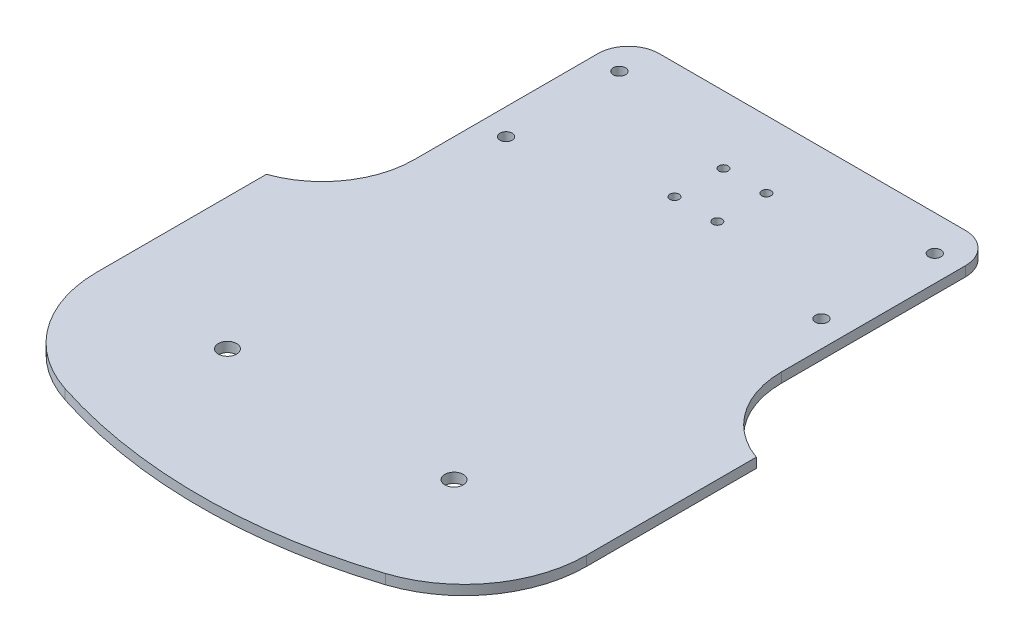
SolidWorks part; units mm, degrees
other "main"
material "Skleněné vlákno-A"
ref_plane "Přední rovina" through (0, 0, 0) normal (0, 0, 1) x (1, 0, 0)
ref_plane "Horní rovina" through (0, 0, 0) normal (0, 1, 0) x (1, 0, 0)
ref_plane "Pravá rovina" through (0, 0, 0) normal (1, 0, 0) x (0, 0, -1)
sketch "Skica1" plane through (0, 0, 0) normal (0, 1, 0) x (1, 0, 0)
  line L0 (0, 0) -> (-30, 0) construction
  line L1 (-25, 15) -> (25, 15)
  line L2 (-30, 10) -> (-30, -20)
  line L3 (0, -85) -> (-40, -85) construction
  line L4 (30, 10) -> (30, -20)
  line L5 (-40, -61.8466) -> (-40, -34.1421)
  line L6 (0, -154.3556) -> (0, 117.2396) construction
  line L7 (40, -61.8466) -> (40, -34.1421)
  arc A0 (-30, -20) -> (-40, -34.1421) centre (-45, -20) cw
  arc A1 (-25, 15) -> (-30, 10) centre (-25, 10) ccw
  arc A2 (26.1538, -80.8763) -> (-26.1538, -80.8763) centre (0, 0) cw
  arc A3 (25, 15) -> (30, 10) centre (25, 10) cw
  arc A4 (30, -20) -> (40, -34.1421) centre (45, -20) ccw
  arc A5 (40, -61.8466) -> (26.1538, -80.8763) centre (20, -61.8466) cw
  arc A6 (-26.1538, -80.8763) -> (-40, -61.8466) centre (-20, -61.8466) cw
  point P8 (32.3438, 20)
  point P13 (-30, 15)
  point P24 (0, 15)
  point P26 (40, -75)
  point P29 (-40, -75)
  dimension "D4" = 5
  dimension "D2" = 100
  dimension "D5" = 80
  dimension "D7" = 15
  dimension "D8" = 20
  dimension "D1" = 60
  dimension "D3" = 15
  dimension "D6" = 20
extrude "Přidat vysunutím1" add sketch "Skica1" along normal mid plane 1.6
sketch "Skica2" plane through (0, -0.8, 0) normal (0, -1, 0) x (1, 0, 0)
  circle A0 centre (-25.75, -9.25) radius 1 construction
  circle A1 centre (-25.75, -9.25) radius 1
  circle A2 centre (-25.75, 9.25) radius 1 construction
  circle A3 centre (25.75, 9.25) radius 1 construction
  circle A4 centre (25.75, -9.25) radius 1 construction
  circle A5 centre (-25.75, 9.25) radius 1
  circle A6 centre (25.75, 9.25) radius 1
  circle A7 centre (25.75, -9.25) radius 1
extrude "Odebrat vysunutím1" cut sketch "Skica2" against normal through all
sketch "Skica3" plane through (0, -0.8, 0) normal (0, -1, 0) x (1, 0, 0)
  line L0 (0, 0) -> (14.3407, 0) construction
  line L1 (0, 0) -> (0, 8.7788) construction
  circle A0 centre (-3.5, 4) radius 0.75
  circle A1 centre (3.5, 4) radius 0.75
  circle A2 centre (-3.5, -4) radius 0.75
  circle A3 centre (3.5, -4) radius 0.75
  dimension "D1" = 8
  dimension "D2" = 7
  dimension "D3" = 1.5
extrude "Odebrat vysunutím2" cut sketch "Skica3" against normal through all
sketch "Skica8" plane through (0, -0.8, 0) normal (0, -1, 0) x (1, 0, 0)
  circle A1 centre (18.5, 62) radius 1.5 construction
  circle A3 centre (-18.5, 62) radius 1.5 construction
  circle A4 centre (18.5, 62) radius 1.5
  circle A5 centre (-18.5, 62) radius 1.5
extrude "Odebrat vysunutím4" cut sketch "Skica8" against normal through all
sketch "Skica5" plane through (0, -0.8, 0) normal (0, -1, 0) x (1, 0, 0)
  line L0 (40, 61.8466) -> (40, 34.1421) construction
  line L2 (-40, 34.1421) -> (-40, 61.8466) construction
  arc A0 (26.1538, 80.8763) -> (-26.1538, 80.8763) centre (0, 0) ccw construction
  circle A1 centre (-22.7593, 74.6057) radius 0.25
  circle A2 centre (-30, 72) radius 0.25
  circle A3 centre (-15.2971, 76.4853) radius 0.25
  circle A4 centre (-7.6859, 77.6204) radius 0.25
  circle A5 centre (0, 78) radius 0.25
  circle A6 centre (7.6859, 77.6204) radius 0.25
  circle A7 centre (15.2971, 76.4853) radius 0.25
  circle A8 centre (22.7593, 74.6057) radius 0.25
  circle A9 centre (30, 72) radius 0.25
  arc A10 (26.1538, 80.8763) -> (-26.1538, 80.8763) centre (0, 0) ccw construction
  point P28 (0, 85)
  dimension "D1" = 7
  dimension "D4" = 0.5
  dimension "D5" = 10
  dimension "D6" = 7
  dimension "D7" = 7
  dimension "D8" = 7.6953
  dimension "D2" = 10
  dimension "D3" = 9
sketch "keepouts" plane through (0, -0.8, 0) normal (0, -1, 0) x (1, 0, 0)
  line L0 (-21.5, 7.5) -> (-21.5, 8.75) construction
  line L1 (-29.75, 7.5) -> (-18.75, 7.5) construction
  line L2 (-21.5, -8.75) -> (-21.5, -7.5) construction
  line L3 (-21.5, -7.5) -> (-18.75, -7.5) construction
  line L4 (-21.5, 7.5) -> (-21.5, 8.75)
  line L5 (-21.5, 7.5) -> (-18.75, 7.5)
  line L6 (-21.5, -8.75) -> (-21.5, -7.5)
  line L7 (-21.5, -7.5) -> (-18.75, -7.5)
  line L8 (18.5, 11) -> (18.5, 29)
  line L9 (-16.5, 9) -> (16.5, 9)
  line L10 (-18.5, 29) -> (-18.5, 11)
  line L11 (16.5, 31) -> (-16.5, 31)
  line L12 (18.5, 11) -> (18.5, 29)
  line L13 (-16.5, 9) -> (16.5, 9)
  line L14 (-18.5, 29) -> (-18.5, 11)
  line L15 (16.5, 31) -> (-16.5, 31)
  line L16 (-4.8, -2.5) -> (-4.8, 2.5) construction
  line L17 (-18.75, 7.5) -> (-4.8, 7.5)
  line L18 (21.5, 8.75) -> (21.5, 7.5) construction
  line L19 (-18.75, -7.5) -> (-4.8, -7.5)
  line L20 (-4.8, 7.5) -> (-4.8, -7.5)
  line L21 (21.5, 8.75) -> (21.5, 7.5)
  line L22 (18.75, 7.5) -> (29.75, 7.5) construction
  line L23 (18.75, 7.5) -> (21.5, 7.5)
  line L24 (29.75, -7.5) -> (18.75, -7.5) construction
  line L25 (21.5, -7.5) -> (21.5, -8.75) construction
  line L26 (21.5, -7.5) -> (18.75, -7.5)
  line L27 (21.5, -7.5) -> (21.5, -8.75)
  line L28 (4.8, 2.5) -> (4.8, -2.5) construction
  line L29 (18.75, 7.5) -> (4.8, 7.5)
  line L31 (18.75, -7.5) -> (4.8, -7.5)
  line L32 (4.8, 7.5) -> (4.8, -7.5)
  line L37 (22.5, 56) -> (22.5, 62) construction
  line L38 (22.5, 56) -> (22.5, 62)
  line L40 (14.5, 62) -> (14.5, 56) construction
  line L41 (14.5, 56) -> (22.5, 56) construction
  line L47 (14.5, 62) -> (14.5, 56)
  line L48 (-22.5, 62) -> (-22.5, 56) construction
  line L49 (-14.5, 56) -> (-14.5, 62) construction
  line L51 (-22.5, 62) -> (-22.5, 56)
  line L52 (-14.5, 56) -> (-14.5, 62)
  line L53 (-22.5, 56) -> (-14.5, 56) construction
  line L54 (14.5, 56) -> (22.5, 56)
  line L55 (-22.5, 56) -> (-14.5, 56)
  arc A0 (-21.5, 8.75) -> (-30, 8.75) centre (-25.75, 8.75) ccw construction
  arc A1 (-30, -8.75) -> (-21.5, -8.75) centre (-25.75, -8.75) ccw construction
  arc A2 (-21.5, 8.75) -> (-30, 8.75) centre (-25.75, 8.75) ccw
  arc A3 (-30, -8.75) -> (-21.5, -8.75) centre (-25.75, -8.75) ccw
  arc A4 (30, 8.75) -> (21.5, 8.75) centre (25.75, 8.75) ccw construction
  arc A5 (30, 8.75) -> (21.5, 8.75) centre (25.75, 8.75) ccw
  arc A6 (21.5, -8.75) -> (30, -8.75) centre (25.75, -8.75) ccw construction
  arc A7 (21.5, -8.75) -> (30, -8.75) centre (25.75, -8.75) ccw
  arc A8 (18.5, 29) -> (16.5, 31) centre (16.5, 29) ccw
  arc A9 (16.5, 9) -> (18.5, 11) centre (16.5, 11) ccw
  arc A10 (-18.5, 11) -> (-16.5, 9) centre (-16.5, 11) ccw
  arc A11 (-16.5, 31) -> (-18.5, 29) centre (-16.5, 29) ccw
  arc A12 (18.5, 29) -> (16.5, 31) centre (16.5, 29) ccw
  arc A13 (16.5, 9) -> (18.5, 11) centre (16.5, 11) ccw
  arc A14 (-18.5, 11) -> (-16.5, 9) centre (-16.5, 11) ccw
  arc A15 (-16.5, 31) -> (-18.5, 29) centre (-16.5, 29) ccw
  arc A17 (22.5, 62) -> (14.5, 62) centre (18.5, 62) ccw construction
  arc A19 (22.5, 62) -> (14.5, 62) centre (18.5, 62) ccw
  arc A20 (-14.5, 62) -> (-22.5, 62) centre (-18.5, 62) ccw construction
  arc A21 (-14.5, 62) -> (-22.5, 62) centre (-18.5, 62) ccw
  dimension "D1" = 1
